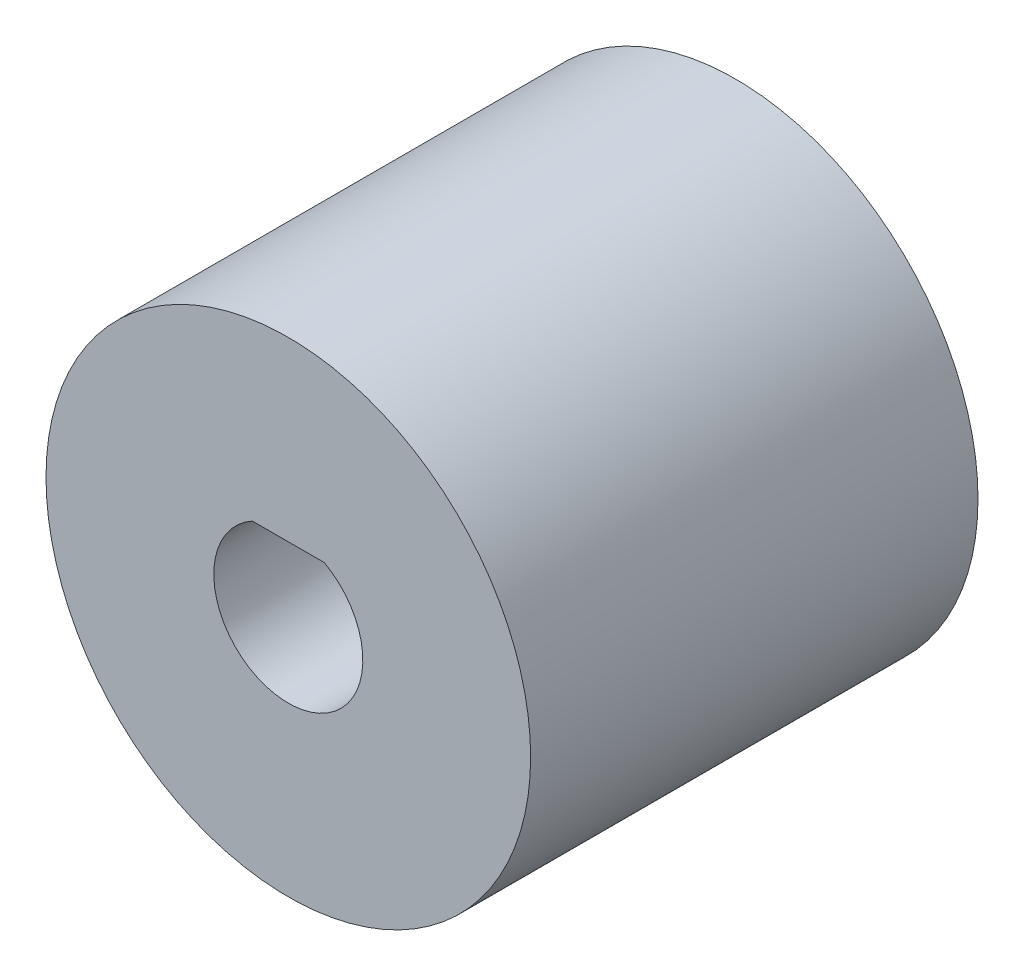
SolidWorks part; units mm, degrees
ref_plane "Front Plane" through (0, 0, 0) normal (0, 0, 1) x (1, 0, 0)
ref_plane "Top Plane" through (0, 0, 0) normal (0, 1, 0) x (1, 0, 0)
ref_plane "Right Plane" through (0, 0, 0) normal (1, 0, 0) x (0, 0, -1)
sketch "Sketch3" plane through (0, 0, 0) normal (0, 0, 1) x (1, 0, 0)
  line L2 (1.9313, 3.5) -> (-1.9313, 3.5)
  arc A0 (-1.9313, 3.5) -> (1.9313, 3.5) centre (0, 0) ccw
  circle A3 centre (0, 0) radius 13
  dimension "D1" = 7.995
extrude "Boss-Extrude1" add sketch "Sketch3" against normal up to surface (24 mm away)
